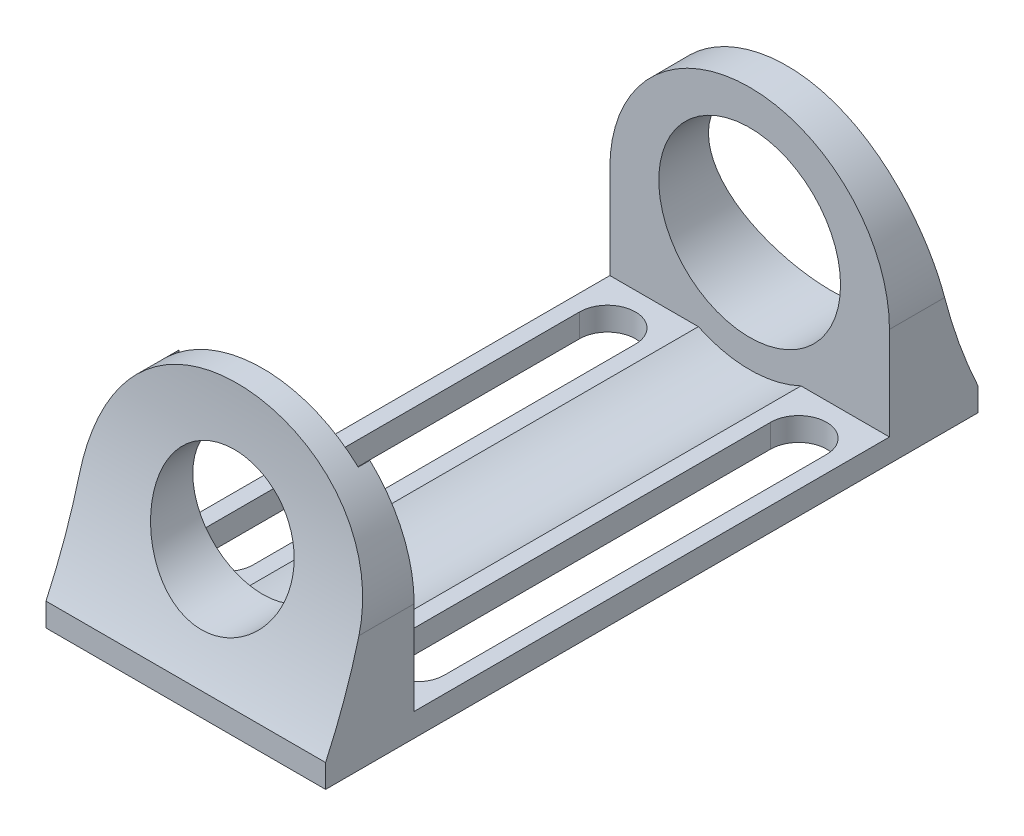
SolidWorks part; units mm, degrees
ref_plane "Plano frontal" through (0, 0, 0) normal (0, 0, 1) x (1, 0, 0)
ref_plane "Plano superior" through (0, 0, 0) normal (0, 1, 0) x (1, 0, 0)
ref_plane "Plano direito" through (0, 0, 0) normal (1, 0, 0) x (0, 0, -1)
sketch "Esboço1" plane through (0, 0, 0) normal (1, 0, 0) x (0, 0, -1)
  line L0 (0, 0) -> (70, 0)
  line L1 (70, 0) -> (70, 5)
  line L3 (59, 55) -> (51, 55)
  line L4 (51, 55) -> (51, 5)
  line L5 (51, 5) -> (0, 5)
  line L6 (0, 5) -> (0, 0)
  line L7 (59, 55) -> (59, 8.0983) construction
  arc A0 (59, 55) -> (70, 5) centre (178.1364, 55) ccw
  dimension "D1" = 51
  dimension "D2" = 5
  dimension "D3" = 8
  dimension "D4" = 5
  dimension "D5" = 50
  dimension "D6" = 70
extrude "Ressalto-extrusão1" add sketch "Esboço1" along normal blind 60
sketch "Esboço2" plane through (0, 0, -51) normal (0, 0, 1) x (1, 0, 0)
  line L0 (30, 28) -> (30, 5) construction
  line L1 (60, 5) -> (0, 5) construction
  line L2 (60, 5) -> (0, 5) construction
  circle A0 centre (30, 28) radius 25.5
  dimension "D1" = 51
  dimension "D2" = 23
extrude "Corte-extrusão1" cut sketch "Esboço2" along normal through all
sketch "Esboço3" plane through (0, 0, -51) normal (0, 0, 1) x (1, 0, 0)
  circle A0 centre (30, 28) radius 25.5 construction
  arc A1 (18.9886, 5) -> (41.0114, 5) centre (30, 28) ccw construction
  circle A2 centre (30, 28) radius 17.5
  dimension "D1" = 35
extrude "Corte-extrusão2" cut sketch "Esboço3" against normal through all
sketch "Esboço4" plane through (0, 0, -51) normal (0, 0, 1) x (1, 0, 0)
  line L1 (60, 55) -> (0, 55) construction
  line L2 (0, 55) -> (0, 5) construction
  line L3 (60, 55) -> (60, 5) construction
  line L4 (60, 55) -> (60, 25)
  line L5 (0, 55) -> (0, 25)
  line L6 (60, 55) -> (0, 55)
  arc A0 (60, 25) -> (0, 25) centre (30, 25) ccw
  line M6 (60, 5) -> (60, 55)
  line M7 (60, 55) -> (0, 55)
  line M8 (0, 55) -> (0, 5)
extrude "Corte-extrusão3" cut sketch "Esboço4" against normal blind 60 contours A0 L6 M8 | A0 M6 M7
mirror "Espelhar2" about plane through (60, 5, 0) normal (0, 0, -1) of "Ressalto-extrusão1"
sketch "Esboço5" plane through (0, 0, 0) normal (0, 0, -1) x (-1, 0, 0)
  line L1 (-18.9886, 5) -> (-41.0114, 5)
  line L2 (-18.9886, 5) -> (-41.0114, 5)
  arc A1 (-41.0114, 5) -> (-18.9886, 5) centre (-30, 28) ccw
  arc A2 (-41.0114, 5) -> (-18.9886, 5) centre (-30, 28) ccw
  dimension "D1" = 0
sketch "Esboço6" plane through (0, 0, 51) normal (0, 0, -1) x (-1, 0, 0)
  line L4 (-60, 25) -> (-60, 5)
  line L5 (0, 5) -> (0, 25)
  line L6 (-18.9886, 5) -> (0, 5)
  line L7 (-60, 5) -> (-41.0114, 5)
  line L13 (0, 5) -> (0, 55)
  line L14 (0, 55) -> (-60, 55)
  line L15 (-60, 55) -> (-60, 5)
  line L16 (-60, 5) -> (0, 5)
  line L18 (0, 25) -> (0, 55)
  line L19 (0, 55) -> (-60, 55)
  line L20 (-60, 55) -> (-60, 5)
  circle A0 centre (-30, 28) radius 17.5 construction
  arc A2 (0, 25) -> (-60, 25) centre (-30, 25) ccw
  arc A3 (-41.0114, 5) -> (-18.9886, 5) centre (-30, 28) ccw
  arc A4 (0, 25) -> (-60, 25) centre (-30, 25) ccw
  circle A7 centre (-30, 28) radius 17.5 construction
  circle A8 centre (-30, 28) radius 15
  line M13 (0, 5) -> (0, 55)
  line M14 (0, 55) -> (-60, 55)
  line M15 (-60, 55) -> (-60, 5)
  dimension "D3" = 2.5
  dimension "D1" = 0
  dimension "D2" = 0
sketch "Esboço7" plane through (0, 55, 0) normal (0, 1, 0) x (1, 0, 0)
  line L0 (0, -51) -> (60, -51) construction
  line L1 (50.5, -53.5) -> (9.5, -53.5)
  line L2 (50.5, -53.5) -> (50.5, -51)
  line L3 (50.5, -51) -> (9.5, -51)
  line L4 (9.5, -53.5) -> (9.5, -51)
  point P6 (30, -51)
  dimension "D1" = 41
  dimension "D2" = 2.5
extrude "Corte-extrusão6" cut sketch "Esboço7" against normal up to surface (50 mm away) up to face at (30, 5, -12.75)
extrude "Corte-extrusão7" cut sketch "Esboço6" against normal through all contours A7 | A4 L19 M15 | A4 M13 M14 | A8
extrude "Corte-extrusão8" cut sketch "Esboço5" against normal up to surface (53.5 mm away) contours A2 L2 up to face at (30, 13, 53.5)
sketch "Esboço8" plane through (0, 5, 0) normal (0, 1, 0) x (1, 0, 0)
  line L0 (9.4943, -41) -> (9.4943, 41) construction
  line L1 (3.5, -41) -> (3.5, 41)
  line L2 (15.4886, -41) -> (15.4886, 41)
  line L3 (30, -53.5) -> (30, 59) construction
  line L4 (0, 0) -> (18.9886, 0) construction
  line L5 (0, 51) -> (0, -51) construction
  line L6 (18.9886, 51) -> (18.9886, -53.5) construction
  line L7 (41.0114, -53.5) -> (18.9886, -53.5) construction
  line L8 (60, 0) -> (41.0114, 0) construction
  line L9 (50.5057, -41) -> (50.5057, 41) construction
  line L10 (56.5, -41) -> (56.5, 41)
  line L11 (44.5114, -41) -> (44.5114, 41)
  arc A0 (3.5, -41) -> (15.4886, -41) centre (9.4943, -41) ccw
  arc A1 (15.4886, 41) -> (3.5, 41) centre (9.4943, 41) ccw
  arc A2 (56.5, -41) -> (44.5114, -41) centre (50.5057, -41) cw
  arc A3 (44.5114, 41) -> (56.5, 41) centre (50.5057, 41) cw
  spline S0 degree 3 poles (60, 62.839) (60, 62.3371) (59.8156, 61.8916) (59.2635, 61.3013) (59.0332, 61.1176) (58.4767, 60.7751) (58.149, 60.6163) (57.0411, 60.1851) (56.1323, 59.9538) (54.7819, 59.7201) (54.501, 59.6761) (53.9171, 59.5935) (53.6133, 59.5546) (52.6764, 59.4465) (52.0181, 59.3853) (49.9443, 59.2283) (48.4313, 59.1587) (46.3718, 59.0987) (45.9512, 59.0881) (45.1026, 59.0694) (44.6733, 59.0613) (43.3708, 59.0401) (41.5953, 59.02) (39.7429, 59.0105) (37.8514, 59.0041) (36.8818, 59.0024) (33.9626, 58.9995) (31.9928, 59) (28.0052, 59) (26.0449, 58.9995) (23.1526, 59.0024) (22.1966, 59.004) (20.3012, 59.0103) (19.3597, 59.0151) (16.6222, 59.0373) (14.8918, 59.0623) (12.8462, 59.1214) (12.4431, 59.1346) (11.6487, 59.1643) (11.2565, 59.1809) (10.1084, 59.2359) (9.3804, 59.2796) (7.3057, 59.4362) (6.067, 59.5745) (4.7035, 59.8088) (4.4397, 59.8589) (3.9365, 59.9646) (3.6965, 60.0203) (3.0104, 60.1965) (2.186, 60.4555) (1.5386, 60.7672) (0.9802, 61.1079) (0.7449, 61.2937) (0.1844, 61.8891) (0, 62.337) (0, 62.839) knots 0 0 0 0 0.0625 0.0625 0.09375 0.09375 0.125 0.125 0.1875 0.1875 0.203125 0.203125 0.21875 0.21875 0.25 0.25 0.3125 0.3125 0.328125 0.328125 0.34375 0.34375 0.375 0.40625 0.40625 0.4375 0.4375 0.5 0.5 0.5625 0.5625 0.59375 0.59375 0.625 0.625 0.6875 0.6875 0.703125 0.703125 0.71875 0.71875 0.75 0.75 0.8125 0.8125 0.828125 0.828125 0.84375 0.84375 0.875 0.90625 0.90625 0.9375 0.9375 1 1 1 1 construction
  point P2 (9.4943, 0)
  point P7 (9.4943, 0)
  point P26 (50.5057, 0)
  dimension "D1" = 3.5
  dimension "D2" = 82
extrude "Corte-extrusão9" cut sketch "Esboço8" against normal through all
sketch "Esboço9" plane through (0, 0, -51) normal (0, 0, 1) x (1, 0, 0)
  circle A0 centre (30, 28) radius 19.5
  circle A1 centre (30, 28) radius 17.5 construction
  dimension "D1" = 2
extrude "Corte-extrusão10" cut sketch "Esboço9" against normal through all
